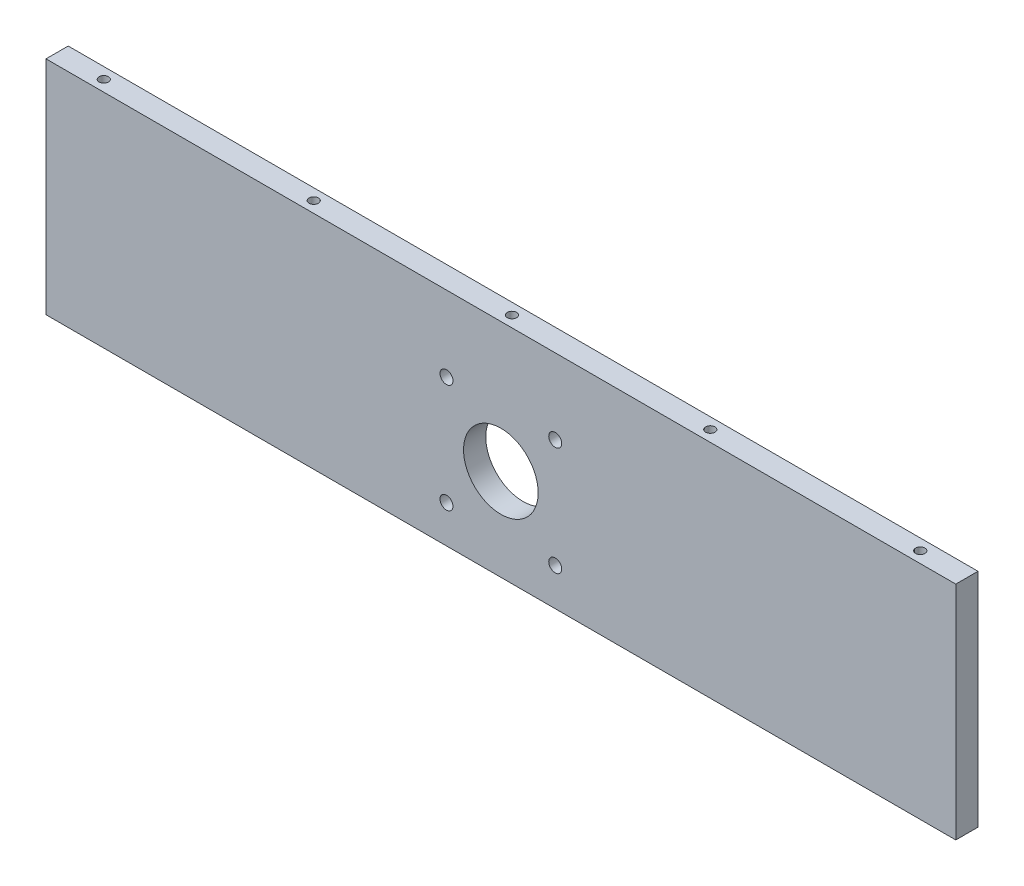
SolidWorks part; units mm, degrees
ref_plane "Plano frontal" through (0, 0, 0) normal (0, 0, 1) x (1, 0, 0)
ref_plane "Plano superior" through (0, 0, 0) normal (0, 1, 0) x (1, 0, 0)
ref_plane "Plano direito" through (0, 0, 0) normal (1, 0, 0) x (0, 0, -1)
sketch "Esboço1" plane through (0, 0, 0) normal (0, 0, 1) x (1, 0, 0)
  line L0 (195, 47.5) -> (-195, -47.5) construction
  line L1 (-195, 47.5) -> (195, 47.5)
  line L2 (-195, 47.5) -> (-195, -47.5)
  line L3 (-195, -47.5) -> (195, -47.5)
  line L4 (195, 47.5) -> (195, -47.5)
  dimension "D1" = 390
  dimension "D2" = 95
extrude "Ressalto-extrusão1" add sketch "Esboço1" along normal blind 9.525
sketch "Esboço3" plane through (0, 0, 9.525) normal (0, 0, 1) x (1, 0, 0)
  line L0 (0, 47.5) -> (0, -47.5) construction
  line L1 (195, 47.5) -> (-195, 47.5) construction
  line L2 (-195, -47.5) -> (195, -47.5) construction
  circle A0 centre (-0.012, -8.12) radius 16
  dimension "D1" = 32
  dimension "D2" = 55.62
extrude "Corte-extrusão2" cut sketch "Esboço3" against normal up to surface (9.525 mm away) up to face at (0, 0, 0)
sketch "Esboço17" plane through (0, 0, 0) normal (0, 0, -1) x (-1, 0, 0)
  line L0 (0.012, 7.88) -> (0.012, -24.12) construction
  line L1 (16.012, -8.12) -> (-15.988, -8.12) construction
  circle A0 centre (23.312, -31.42) radius 2.78
  circle A1 centre (-23.288, -31.42) radius 2.78
  circle A2 centre (23.312, 15.18) radius 2.78
  circle A3 centre (-23.288, 15.18) radius 2.78
  circle A4 centre (0.012, -8.12) radius 16 construction
  dimension "D1" = 5.56
  dimension "D2" = 23.3
  dimension "D3" = 23.3
extrude "Corte-extrusão12" cut sketch "Esboço17" against normal up to surface (9.525 mm away) up to face at (15.988, -8.12, 9.525)
sketch "Esboço18" plane through (0, 47.5, 0) normal (0, 1, 0) x (-1, 0, 0)
  line L0 (195, 4.7625) -> (-195, 4.7625) construction
  line L1 (195, 9.525) -> (195, 0) construction
  line L2 (-195, 9.525) -> (-195, 0) construction
  line L3 (0, 0) -> (0, 9.525) construction
  line L4 (-195, 0) -> (195, 0) construction
  line L5 (-195, 9.525) -> (195, 9.525) construction
  circle A0 centre (-175, 4.7625) radius 2
  circle A1 centre (-85, 4.7625) radius 2
  circle A2 centre (0, 4.7625) radius 2
  circle A3 centre (175, 4.7625) radius 2
  circle A4 centre (85, 4.7625) radius 2
  dimension "D1" = 4
  dimension "D2" = 4
  dimension "D3" = 4
  dimension "D4" = 20
  dimension "D5" = 110
extrude "Corte-extrusão13" cut sketch "Esboço18" against normal blind 20
sketch "Esboço19" plane through (0, -47.5, 0) normal (0, -1, 0) x (1, 0, 0)
  line L0 (-195, 4.7625) -> (195, 4.7625) construction
  line L1 (-195, 9.525) -> (-195, 0) construction
  line L2 (195, 9.525) -> (195, 0) construction
  circle A0 centre (-115, 4.7625) radius 2
  circle A1 centre (0, 4.7625) radius 2
  circle A2 centre (115, 4.7625) radius 2
  dimension "D1" = 4
  dimension "D2" = 4
  dimension "D3" = 4
  dimension "D4" = 80
  dimension "D5" = 80
extrude "Corte-extrusão14" cut sketch "Esboço19" against normal blind 20
